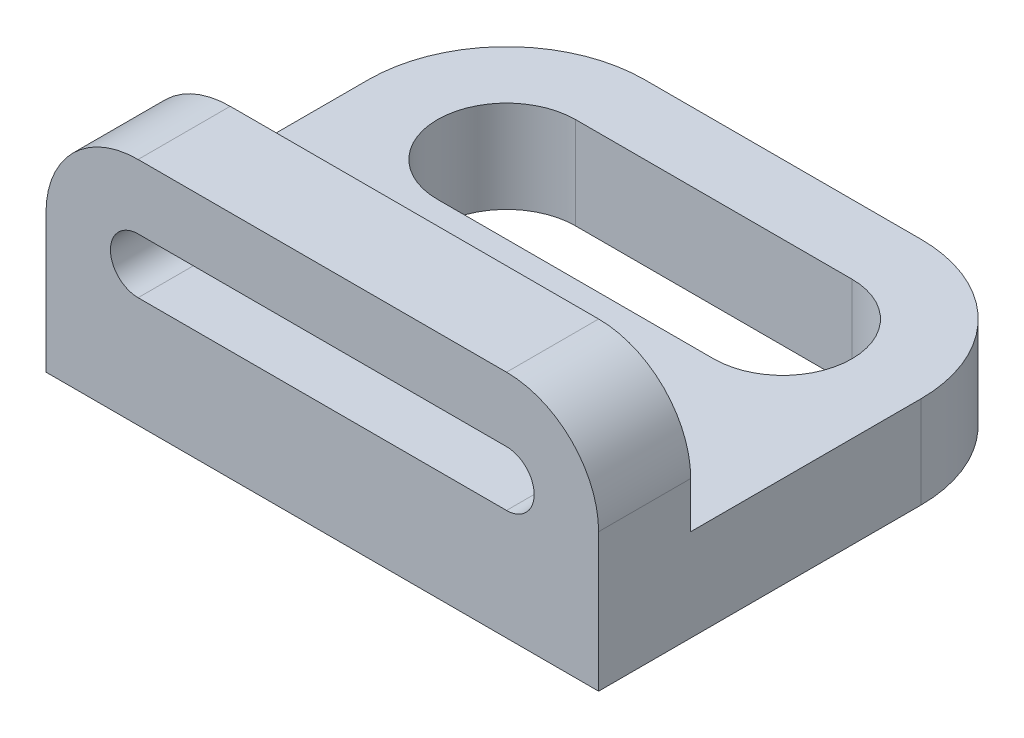
SolidWorks part; units mm, degrees
ref_plane "Front Plane" through (0, 0, 0) normal (0, 0, 1) x (1, 0, 0)
ref_plane "Top Plane" through (0, 0, 0) normal (0, 1, 0) x (1, 0, 0)
ref_plane "Right Plane" through (0, 0, 0) normal (1, 0, 0) x (0, 0, -1)
sketch "Sketch3" plane through (0, 0, 0) normal (1, 0, 0) x (0, 0, -1)
  line L0 (0, 0) -> (100, 0)
  line L1 (100, 0) -> (100, 20)
  line L2 (100, 20) -> (20, 20)
  line L3 (20, 20) -> (20, 50)
  line L4 (0, 50) -> (0, 0)
  line L5 (20, 50) -> (0, 50)
  dimension "100" = 100
  dimension "D2" = 20
  dimension "D3" = 20
  dimension "50" = 50
extrude "Boss-Extrude2" add sketch "Sketch3" along normal blind 120
sketch "Sketch4" plane through (0, 20, 0) normal (0, 1, 0) x (1, 0, 0)
  line L0 (30, 70) -> (90, 70) construction
  line L1 (30, 85) -> (90, 85)
  line L2 (30, 55) -> (90, 55)
  line L3 (120, 0) -> (0, 0) construction
  line L4 (120, 100) -> (120, 20) construction
  arc A0 (30, 85) -> (30, 55) centre (30, 70) ccw
  arc A1 (90, 55) -> (90, 85) centre (90, 70) ccw
  point P2 (60, 70)
  dimension "D1" = 15
  dimension "D2" = 30
  dimension "60" = 60
  dimension "70" = 70
extrude "Cut-Extrude1" cut sketch "Sketch4" against normal through all
fillet "Fillet1" radius 30 1 edges at (0, 10, -100)
fillet "Fillet2" radius 30 1 edges at (120, 10, -100)
fillet "Fillet3" radius 20 2 edges at (120, 50, -10) (0, 50, -10)
sketch "Sketch7" plane through (0, 0, -20) normal (0, 0, -1) x (-1, 0, 0)
  line L0 (-20, 30) -> (-100, 30) construction
  line L1 (-20, 24) -> (-100, 24)
  line L2 (-20, 36) -> (-100, 36)
  line L4 (-120, 20) -> (-120, 30) construction
  line L5 (-90, 0) -> (-30, 0) construction
  arc A0 (-20, 24) -> (-20, 36) centre (-20, 30) ccw
  arc A1 (-100, 36) -> (-100, 24) centre (-100, 30) ccw
  point P2 (-60, 30)
  point P9 (0, 0)
  dimension "D1" = 6
  dimension "80" = 80
  dimension "D2" = 20
  dimension "30" = 30
extrude "Cut-Extrude2" cut sketch "Sketch7" against normal through all
